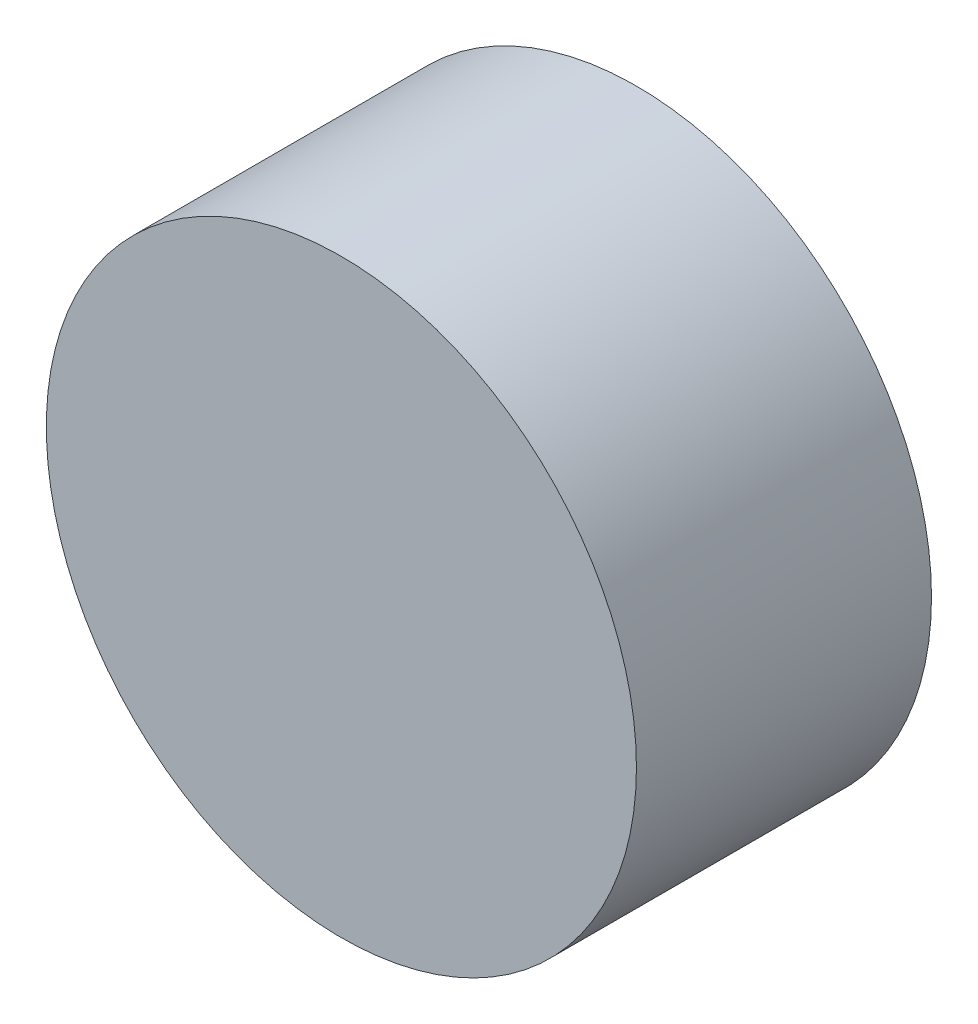
SolidWorks part; units mm, degrees
ref_plane "Front" through (0, 0, 0) normal (0, 0, 1) x (1, 0, 0)
ref_plane "Top" through (0, 0, 0) normal (0, 1, 0) x (1, 0, 0)
ref_plane "Right" through (0, 0, 0) normal (1, 0, 0) x (0, 0, -1)
sketch "Sketch1" plane through (0, 0, 0) normal (0, 0, 1) x (1, 0, 0)
  circle A0 centre (0, 0) radius 10
extrude "Boss-Extrude1" add sketch "Sketch1" along normal blind 10
